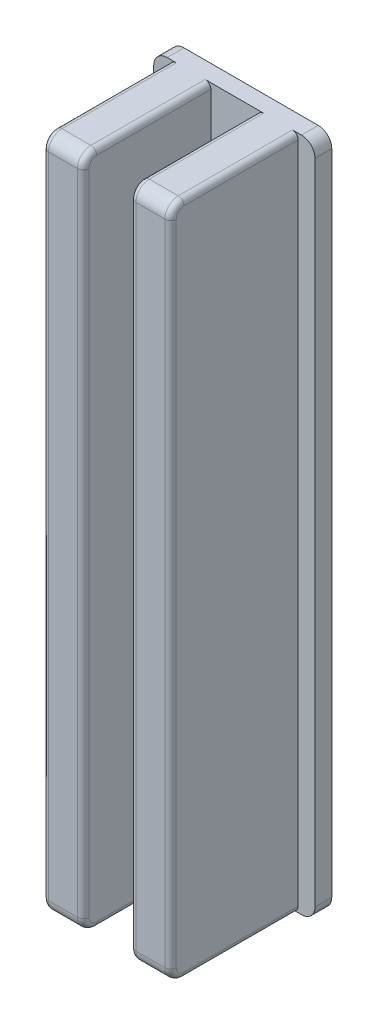
SolidWorks part; units mm, degrees
ref_plane "Front Plane" through (0, 0, 0) normal (0, 0, 1) x (1, 0, 0)
ref_plane "Top Plane" through (0, 0, 0) normal (0, 1, 0) x (1, 0, 0)
ref_plane "Right Plane" through (0, 0, 0) normal (1, 0, 0) x (0, 0, -1)
sketch "Sketch1" plane through (0, 0, 0) normal (0, 0, -1) x (1, 0, 0)
  line L1 (0, 0) -> (24, 0)
  line L2 (0, 0) -> (0, 100.5)
  line L3 (0, 100.5) -> (24, 100.5)
  line L4 (24, 0) -> (24, 100.5)
  dimension "D1" = 24
  dimension "D2" = 100.5
extrude "Boss-Extrude1" add sketch "Sketch1" along normal blind 2.5
fillet "Fillet1" radius 2 4 edges at (0, 0, -1.25) (0, -100.5, -1.25) (24, -100.5, -1.25) (24, 0, -1.25)
sketch "Sketch2" plane through (0, 0, 0) normal (0, 0, 1) x (1, 0, 0)
  line L0 (2, 0) -> (22, 0) construction
  line L1 (8.5, 0) -> (2.5, 0)
  line L2 (8.5, 0) -> (8.5, -100.5)
  line L3 (8.5, -100.5) -> (2.5, -100.5)
  line L4 (2.5, 0) -> (2.5, -100.5)
  line L5 (22, -100.5) -> (2, -100.5) construction
  line L7 (15.5, 0) -> (21.5, 0)
  line L8 (15.5, 0) -> (15.5, -100.5)
  line L9 (15.5, -100.5) -> (21.5, -100.5)
  line L10 (21.5, 0) -> (21.5, -100.5)
  point P12 (12, -100.5)
  dimension "D1" = 6
  dimension "D2" = 6
  dimension "D3" = 3.5
  dimension "D4" = 3.5
extrude "Boss-Extrude2" add sketch "Sketch2" along normal blind 19
sketch "Sketch3" plane through (0, 0, 0) normal (0, 1, 0) x (1, 0, 0)
  line L0 (8.5, -19) -> (8.5, 0) construction
  line L1 (2.5, -19) -> (8.5, -19)
  line L2 (2.5, -19) -> (2.5, -6.5)
  line L3 (2.5, -6.5) -> (8.5, -6.5)
  line L4 (8.5, -19) -> (8.5, -6.5)
  line L5 (21.5, -19) -> (21.5, 0) construction
  line L6 (15.5, -19) -> (21.5, -19)
  line L7 (15.5, -19) -> (15.5, -6.5)
  line L8 (15.5, -6.5) -> (21.5, -6.5)
  line L9 (21.5, -19) -> (21.5, -6.5)
  line L10 (-13.2, 0) -> (13.2, 0) construction
  dimension "D1" = 6.5
extrude "Boss-Extrude3" add sketch "Sketch3" along normal blind 5
fillet "Fillet3" radius 0.5 2 edges at (5.5, 5, 6.5) (18.5, 5, 6.5)
fillet "Fillet4" radius 0.5 2 edges at (5.5, 0, 6.5) (18.5, 0, 6.5)
sketch "Sketch4" plane through (0, 0, -2.5) normal (0, 0, -1) x (-1, 0, 0)
  line L0 (-22, -100.5) -> (-2, -100.5) construction
  line L1 (-5.5, -86.5) -> (-18.5, -86.5) construction
  line L2 (-5.5, -86.5) -> (-5.5, -16) construction
  line L3 (-5.5, -16) -> (-18.5, -16) construction
  line L4 (-18.5, -86.5) -> (-18.5, -16) construction
  line L5 (12.925, 0) -> (-12.925, 0) construction
  line L6 (-21.5, -100.5) -> (-21.5, 0) construction
  line L7 (-2.5, 0) -> (-2.5, -100.5) construction
  circle A0 centre (-5.5, -86.5) radius 1.4
  circle A1 centre (-18.5, -86.5) radius 1.4
  circle A2 centre (-18.5, -16) radius 1.4
  circle A3 centre (-5.5, -16) radius 1.4
  point P6 (-12, -100.5)
  dimension "D5" = 2.8
  dimension "D6" = 2.8
  dimension "D7" = 2.8
  dimension "D8" = 2.8
  dimension "D1" = 14
  dimension "D2" = 16
  dimension "D3" = 3
  dimension "D4" = 3
extrude "Cut-Extrude1" cut sketch "Sketch4" against normal blind 3
sketch "Sketch5" plane through (0, 0, 0) normal (0, 0, 1) x (1, 0, 0)
  line L0 (12, -43) -> (12, -51) construction
  line L1 (0, -98.5) -> (0, -2) construction
  line L3 (12.925, 0) -> (-12.925, 0) construction
  circle A0 centre (12, -43) radius 1.5
  circle A1 centre (12, -51) radius 1.5
  dimension "D4" = 3
  dimension "D5" = 3
  dimension "D1" = 12
  dimension "D2" = 43
  dimension "D3" = 8
extrude "Cut-Extrude2" cut sketch "Sketch5" against normal blind 3
sketch "Sketch6" plane through (0, 0, 0) normal (0, 0, 1) x (1, 0, 0)
  line L1 (10.5, -43) -> (13.5, -43)
  line L2 (10.5, -43) -> (10.5, -51)
  line L3 (10.5, -51) -> (13.5, -51)
  line L4 (13.5, -43) -> (13.5, -51)
  circle A0 centre (12, -43) radius 1.5 construction
  circle A1 centre (12, -51) radius 1.5 construction
  dimension "D1" = 0
  dimension "D2" = 0
extrude "Cut-Extrude3" cut sketch "Sketch6" against normal blind 0.8
sketch "Sketch7" plane through (0, 0, -2.5) normal (0, 0, -1) x (-1, 0, 0)
  text T0 "V0\r\n"
extrude "Cut-Extrude4" cut sketch "Sketch7" against normal blind 0.8
sketch "Sketch8" plane through (2.5, 0, 0) normal (-1, 0, 0) x (0, 0, 1)
  line L0 (12.925, 0) -> (-12.925, 0) construction
  line L1 (-44.0672, 9.7071) -> (57.3601, 9.7071)
  line L2 (-44.0672, 9.7071) -> (-44.0672, 0)
  line L3 (-44.0672, 0) -> (57.3601, 0)
  line L4 (57.3601, 9.7071) -> (57.3601, 0)
  line L5 (-44.0672, 9.7071) -> (57.3601, 0) construction
  line L6 (-44.0672, 0) -> (57.3601, 9.7071) construction
  arc A0 (7, 5) -> (6.5, 4.5) centre (7, 4.5) ccw construction
  point P0 (6.6464, 4.8536)
extrude "Cut-Extrude5" cut sketch "Sketch8" against normal through all
fillet "Fillet2" radius 2 4 edges at (5.5, -100.5, 19) (18.5, -100.5, 19) (18.5, 0, 19) (5.5, 0, 19)
fillet "Fillet5" radius 0.85 20 edges at (2.5, 0, 8.5) (2.5, -100.5, 8.5) (2.5, -99.9142, 18.4142) (8.5, -100.5, 8.5) (8.5, -99.9142, 18.4142) (8.5, 0, 8.5) (15.5, 0, 8.5) (15.5, -100.5, 8.5) (15.5, -99.9142, 18.4142) (21.5, -100.5, 8.5) (21.5, -99.9142, 18.4142) (21.5, 0, 8.5) (2.5, -50.25, 19) (8.5, -50.25, 19) (15.5, -50.25, 19) (21.5, -50.25, 19) (2.5, -0.5858, 18.4142) (8.5, -0.5858, 18.4142) (15.5, -0.5858, 18.4142) (21.5, -0.5858, 18.4142)
sketch "Sketch9" plane through (0, 0, -2.5) normal (0, 0, -1) x (-1, 0, 0)
  text T0 "100.5\r\n\r\n"
extrude "Cut-Extrude6" cut sketch "Sketch9" against normal blind 1
